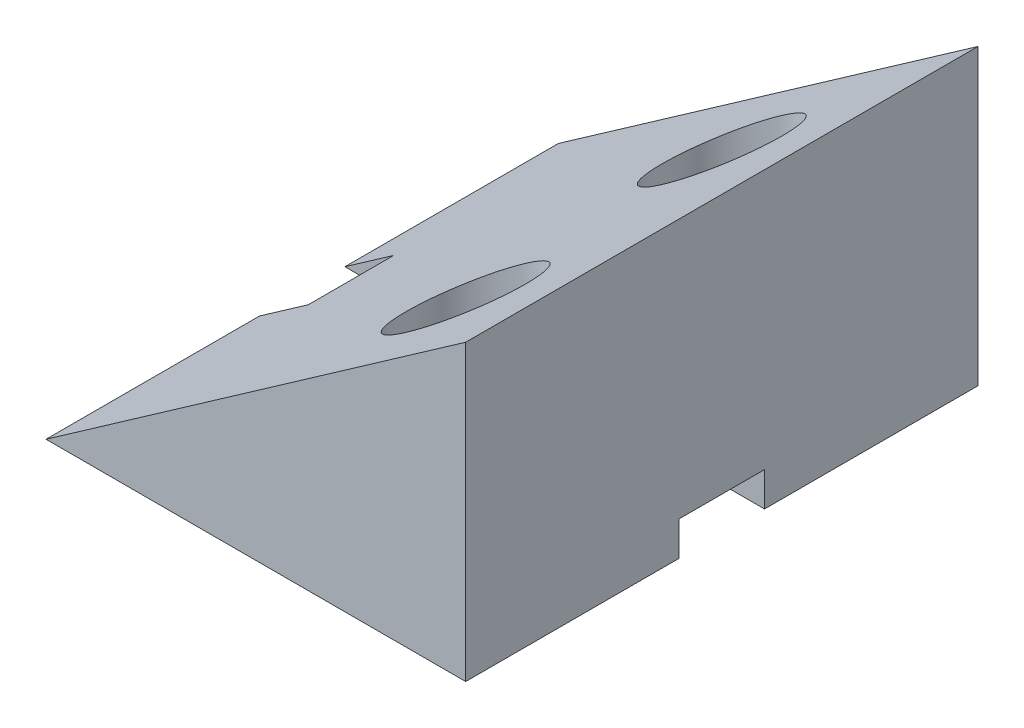
SolidWorks part; units mm, degrees
ref_plane "Plan de face" through (0, 0, 0) normal (0, 0, 1) x (1, 0, 0)
ref_plane "Plan de dessus" through (0, 0, 0) normal (0, 1, 0) x (1, 0, 0)
ref_plane "Plan de droite" through (0, 0, 0) normal (1, 0, 0) x (0, 0, -1)
sketch "Esquisse1" plane through (0, 0, 0) normal (0, 0, 1) x (1, 0, 0)
  line L0 (0, 0) -> (-24.5746, 0)
  line L1 (-24.5746, 0) -> (0, 17.2073)
  line L2 (0, 17.2073) -> (0, 0)
  dimension "D1" = 30
  dimension "D2" = 35
extrude "Boss.-Extru.1" add sketch "Esquisse1" along normal blind 30
ref_plane "Plan1" through (0, 6, 0) normal (0, -1, 0) x (-1, 0, 0)
sketch "Esquisse2" plane through (0, 6, 0) normal (0, -1, 0) x (-1, 0, 0)
  line L0 (0, -30) -> (0, 0) construction
  line L1 (0, -30) -> (0, 0) construction
  line L2 (24.5746, -30) -> (24.5746, 0) construction
  line L3 (0, -30) -> (0, 0) construction
  line L4 (24.5746, -30) -> (24.5746, 0) construction
  line L5 (24.5746, -15) -> (0, -15) construction
  line L6 (24.5746, -30) -> (0, -30) construction
  line L7 (24.5746, 0) -> (0, 0) construction
  line L8 (24.5746, -30) -> (0, -30) construction
  line L9 (24.5746, 0) -> (0, 0) construction
  line L10 (7.5, -15) -> (7.5, 0) construction
  line L11 (7.5, -15) -> (7.5, -30) construction
  circle A0 centre (7.5, -7.5) radius 3.5
  circle A1 centre (7.5, -22.5) radius 3.5
  point P18 (7.5, -22.5)
  point P21 (7.5, -7.5)
  dimension "D1" = 7
  dimension "D2" = 7.5
extrude "Enlèv. mat.-Extru.1" cut sketch "Esquisse2" against normal up to next
sketch "Esquisse3" plane through (0, 6, 0) normal (0, 1, 0) x (1, 0, 0)
  circle A0 centre (-7.5, -7.5) radius 1.75
  circle A1 centre (-7.5, -22.5) radius 1.75
  dimension "D1" = 3.5
extrude "Enlèv. mat.-Extru.2" cut sketch "Esquisse3" against normal up to next contours A1 | A0
sketch "Esquisse4" plane through (0, 0, 0) normal (1, 0, 0) x (0, 0, -1)
  line L0 (-30, 0) -> (0, 0) construction
  line L1 (-17.5, 2) -> (-12.5, 2)
  line L2 (-17.5, 2) -> (-17.5, 0)
  line L3 (-17.5, 0) -> (-12.5, 0)
  line L4 (-12.5, 2) -> (-12.5, 0)
  point P6 (-15, 0)
  point P7 (-15, 0)
  dimension "D1" = 2
  dimension "D2" = 5
extrude "Enlèv. mat.-Extru.3" cut sketch "Esquisse4" against normal up to next
